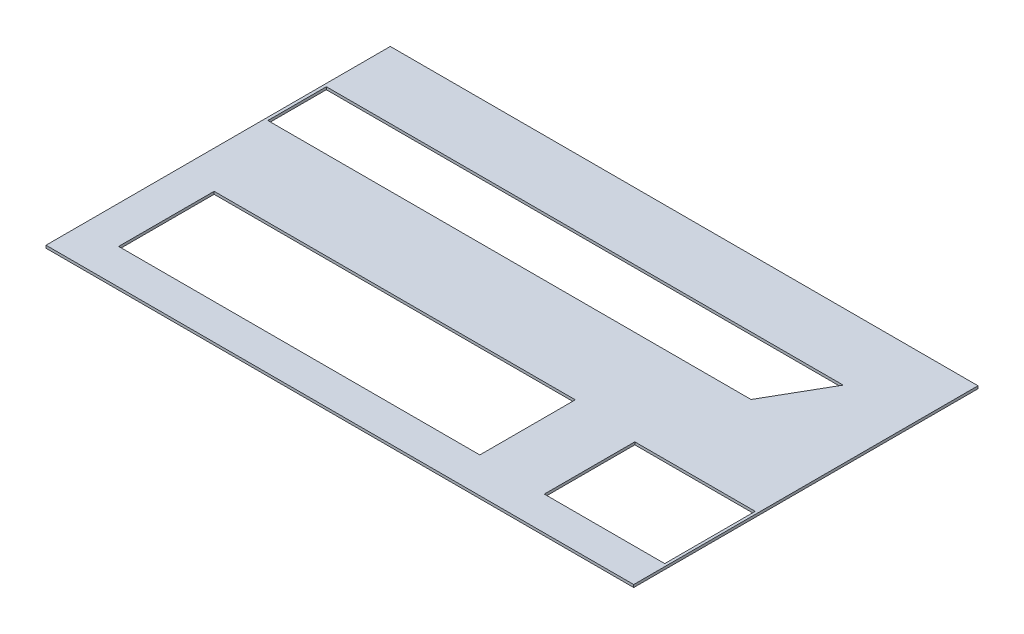
SolidWorks part; units mm, degrees
material "Particle Board"
ref_plane "Front Plane" through (0, 0, 0) normal (0, 0, 1) x (1, 0, 0)
ref_plane "Top Plane" through (0, 0, 0) normal (0, 1, 0) x (1, 0, 0)
ref_plane "Right Plane" through (0, 0, 0) normal (1, 0, 0) x (0, 0, -1)
sketch "Sketch1" plane through (0, 0, 0) normal (0, 1, 0) x (1, 0, 0)
  line L1 (0, 0) -> (1415.68, 0)
  line L2 (0, 0) -> (0, 829.31)
  line L3 (0, 829.31) -> (1415.68, 829.31)
  line L4 (1415.68, 0) -> (1415.68, 829.31)
  dimension "D1" = 1415.68
  dimension "D2" = 829.31
extrude "Boss-Extrude1" add sketch "Sketch1" along normal blind 6.35
sketch "Sketch2" plane through (0, 6.35, 0) normal (0, 1, 0) x (1, 0, 0)
  line L0 (0, 829.31) -> (0, 0) construction
  line L1 (90, 85) -> (960, 85)
  line L2 (90, 85) -> (90, 315)
  line L3 (90, 315) -> (960, 315)
  line L4 (960, 85) -> (960, 315)
  line L5 (0, 0) -> (1415.68, 0) construction
  line L6 (1415.68, 0) -> (1415.68, 829.31) construction
  line L7 (7, 668.31) -> (1252, 668.31)
  line L8 (7, 668.31) -> (7, 527.31)
  line L9 (7, 527.31) -> (1171, 527.31)
  line L11 (1409.33, 299) -> (1119.33, 299)
  line L12 (1409.33, 299) -> (1409.33, 81)
  line L13 (1409.33, 81) -> (1119.33, 81)
  line L14 (1119.33, 299) -> (1119.33, 81)
  line L15 (1252, 668.31) -> (1171, 527.31)
  line L16 (1415.68, 829.31) -> (0, 829.31) construction
  dimension "D1" = 870
  dimension "D2" = 230
  dimension "D3" = 90
  dimension "D4" = 85
  dimension "D5" = 81
  dimension "D6" = 218
  dimension "D7" = 6.35
  dimension "D8" = 290
  dimension "D9" = 7
  dimension "D10" = 1245
  dimension "D11" = 1164
  dimension "D12" = 161
  dimension "D13" = 141
extrude "Cut-Extrude1" cut sketch "Sketch2" against normal up to next
